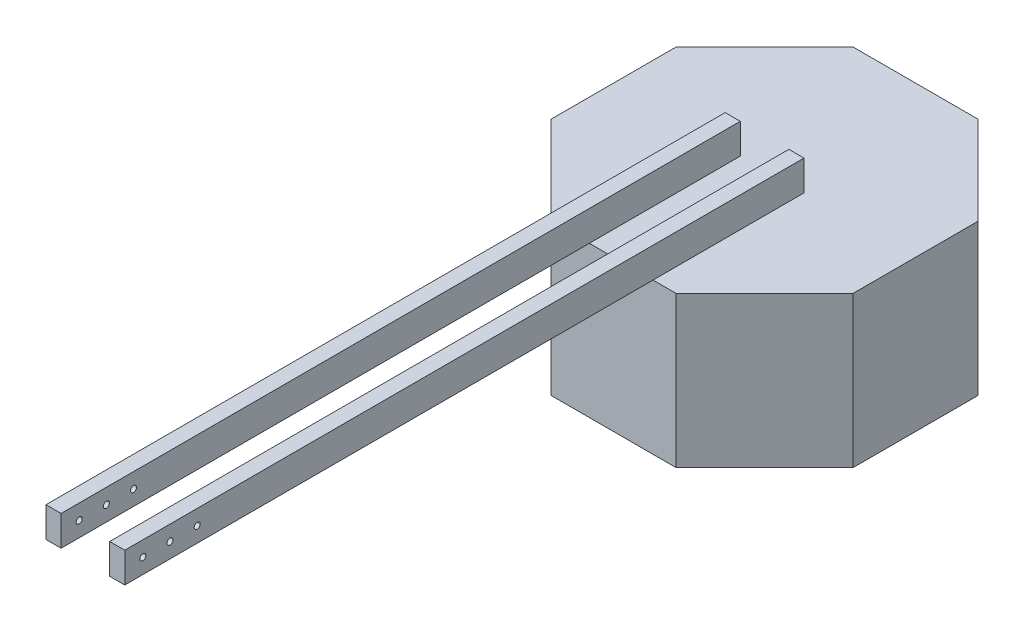
SolidWorks part; units mm, degrees
ref_plane "Front Plane" through (0, 0, 0) normal (0, 0, 1) x (1, 0, 0)
ref_plane "Top Plane" through (0, 0, 0) normal (0, 1, 0) x (1, 0, 0)
ref_plane "Right Plane" through (0, 0, 0) normal (1, 0, 0) x (0, 0, -1)
sketch "Sketch1" plane through (0, 0, 0) normal (0, 1, 0) x (1, 0, 0)
  line L0 (100, -41.4214) -> (100, 41.4214)
  line L1 (41.4214, 100) -> (-41.4214, 100)
  line L2 (-41.4214, 100) -> (-100, 41.4214)
  line L3 (-100, 41.4214) -> (-100, -41.4214)
  line L4 (-100, -41.4214) -> (-41.4214, -100)
  line L5 (-41.4214, -100) -> (41.4214, -100)
  line L6 (41.4214, -100) -> (100, -41.4214)
  line L7 (100, 41.4214) -> (41.4214, 100)
  circle A0 centre (0, 0) radius 100 construction
  dimension "D1" = 200
extrude "Boss-Extrude1" add sketch "Sketch1" along normal blind 100
sketch "Sketch2" plane through (0, 100, 0) normal (0, 1, 0) x (1, 0, 0)
  line L0 (0, 0) -> (0, 210.8552) construction
  line L2 (-26.1, 0) -> (-16.1, 0)
  line L3 (-26.1, 0) -> (-26.1, -450)
  line L4 (-26.1, -450) -> (-16.1, -450)
  line L5 (-16.1, 0) -> (-16.1, -450)
  line L6 (-26.1, 0) -> (-16.1, -450) construction
  line L7 (-26.1, -450) -> (-16.1, 0) construction
  line L8 (26.1, 0) -> (16.1, 0)
  line L9 (16.1, 0) -> (16.1, -450)
  line L10 (26.1, 0) -> (26.1, -450)
  line L11 (26.1, -450) -> (16.1, -450)
  point P3 (-21.1, -225)
  dimension "D1" = 16.1
  dimension "D2" = 10
  dimension "D3" = 450
extrude "Boss-Extrude2" add sketch "Sketch2" along normal blind 20
sketch "Sketch3" plane through (-26.1, 0, 0) normal (-1, 0, 0) x (0, 0, 1)
  line L0 (450, 110) -> (342.8414, 110) construction
  line L1 (450, 120) -> (450, 100) construction
  circle A0 centre (438, 110) radius 2
  circle A1 centre (420, 110) radius 2
  circle A2 centre (402, 110) radius 2
  dimension "D1" = 18
  dimension "D2" = 18
  dimension "D3" = 12
  dimension "D4" = 4
extrude "Cut-Extrude1" cut sketch "Sketch3" against normal through all
